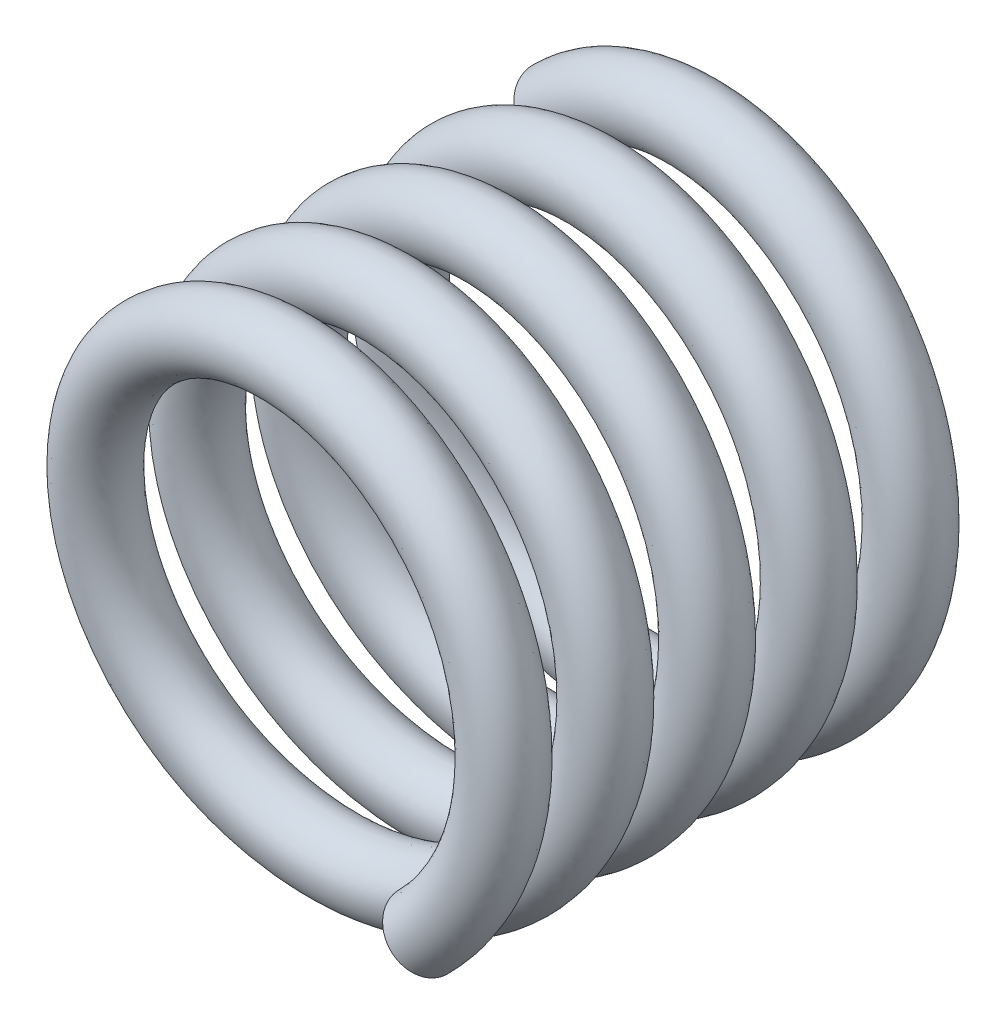
SolidWorks part; units mm, degrees
ref_plane "Front Plane" through (0, 0, 0) normal (0, 0, 1) x (1, 0, 0)
ref_plane "Top Plane" through (0, 0, 0) normal (0, 1, 0) x (1, 0, 0)
ref_plane "Right Plane" through (0, 0, 0) normal (1, 0, 0) x (0, 0, -1)
sketch "Sketch1" plane through (0, 0, 0) normal (0, 0, 1) x (1, 0, 0)
  circle A0 centre (0, 0) radius 2.5
  dimension "D1" = 5
curve "Helix/Spiral1" pitch 1.1111 height 5 turns 4.5 parameters "Inaltime arc"=5
sweep "Sweep1" add path "Helix/Spiral1" circular profile diameter 0.75 parameters "D3"=0.75
sketch "Sketch12" plane through (0, 0, 0) normal (1, 0, 0) x (0, 0, -1)
  line L0 (-12.0452, -9.2722) -> (-12.0452, 8.3804)
split "Split1" bodies to split 101
sketch "Sketch14" plane through (0, 0, 0) normal (0, 1, 0) x (1, 0, 0)
  line L0 (-10.6815, 0) -> (8.2493, 0)
split "Split2" bodies to split 103 resulting bodies 105
